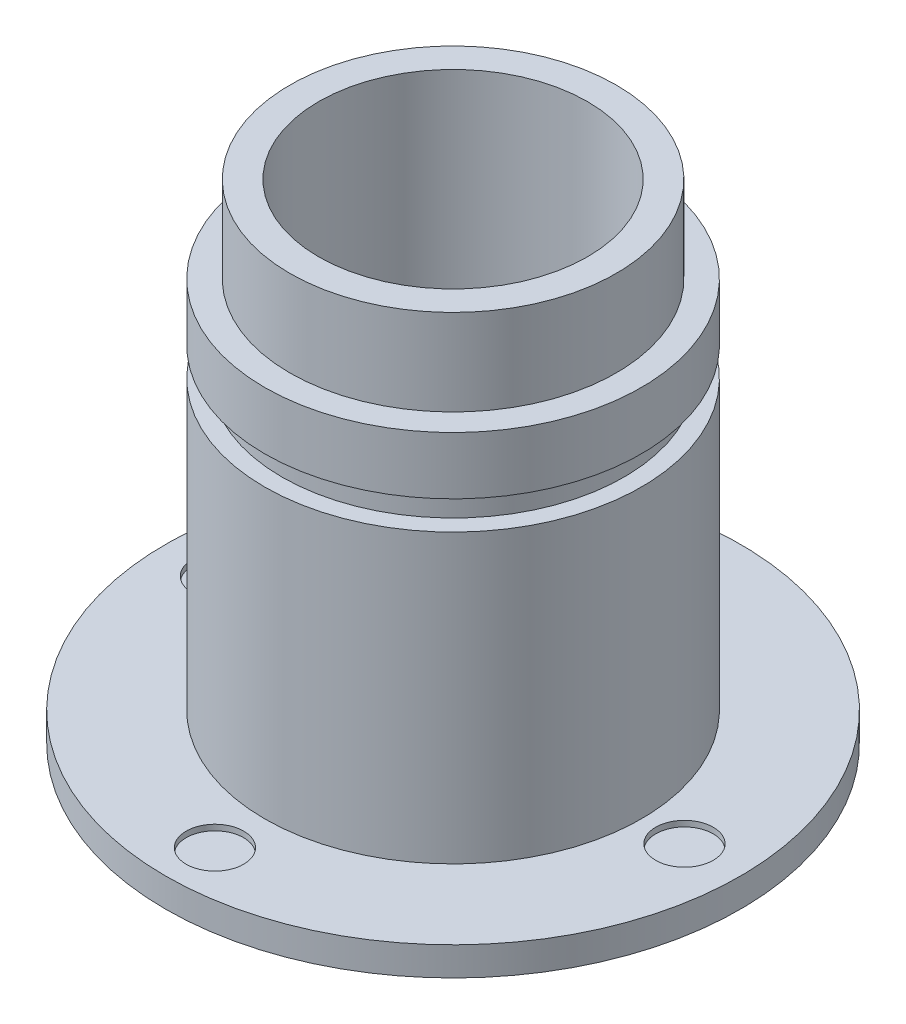
SolidWorks part; units mm, degrees
ref_plane "Front Plane" through (0, 0, 0) normal (0, 0, 1) x (1, 0, 0)
ref_plane "Top Plane" through (0, 0, 0) normal (0, 1, 0) x (1, 0, 0)
ref_plane "Right Plane" through (0, 0, 0) normal (1, 0, 0) x (0, 0, -1)
sketch "Sketch1" plane through (0, 0, 0) normal (0, 0, 1) x (1, 0, 0)
  line L0 (0, 71.3241) -> (0, -89.6938) construction
  line L1 (0, -77.6741) -> (-127, -77.6741)
  line L2 (-127, -77.6741) -> (-127, -64.9741)
  line L3 (-127, -64.9741) -> (-83.2304, -64.9741)
  line L4 (-83.2304, -64.9741) -> (-83.2304, -14.1741)
  line L5 (-83.2304, -14.1741) -> (-83.2304, 62.0259)
  line L6 (-83.2304, 62.0259) -> (-75.6104, 62.0259)
  line L7 (-75.6104, 62.0259) -> (-75.6104, 74.7259)
  line L8 (-75.6104, 74.7259) -> (-83.2304, 74.7259)
  line L9 (-83.2304, 74.7259) -> (-83.2304, 100.1259)
  line L10 (-83.2304, 100.1259) -> (-72.1179, 100.1259)
  line L11 (-72.1179, 100.1259) -> (-72.1179, 138.2259)
  line L12 (-72.1179, 138.2259) -> (-59.4179, 138.2259)
  line L13 (-59.4179, 138.2259) -> (-59.4179, -64.9741)
  line L14 (-59.4179, -64.9741) -> (0, -64.9741)
  line L15 (0, -64.9741) -> (0, -77.6741)
  dimension "D1" = 12.7
  dimension "D2" = 127
  dimension "D3" = 50.8
  dimension "D4" = 76.2
  dimension "D5" = 7.62
  dimension "D6" = 7.62
  dimension "D7" = 12.7
  dimension "D8" = 25.4
  dimension "D9" = 38.1
  dimension "D10" = 12.7
revolve "Revolve1" add sketch "Sketch1" angle 360 about L0
sketch "Sketch2" plane through (0, 0, 0) normal (0, 1, 0) x (1, 0, 0)
  circle A0 centre (-102.6083, 0) radius 12.7
  circle A1 centre (0, -105.2348) radius 12.7
  circle A2 centre (102.2581, 0) radius 12.7
  circle A3 centre (0, 99.2814) radius 12.7
  dimension "D1" = 25.4
  dimension "D2" = 25.4
  dimension "D3" = 25.4
  dimension "D4" = 25.4
extrude "Cut-Extrude1" cut sketch "Sketch2" along a picked direction on the side against the normal offset from surface (67.5141 mm away) 2.54
